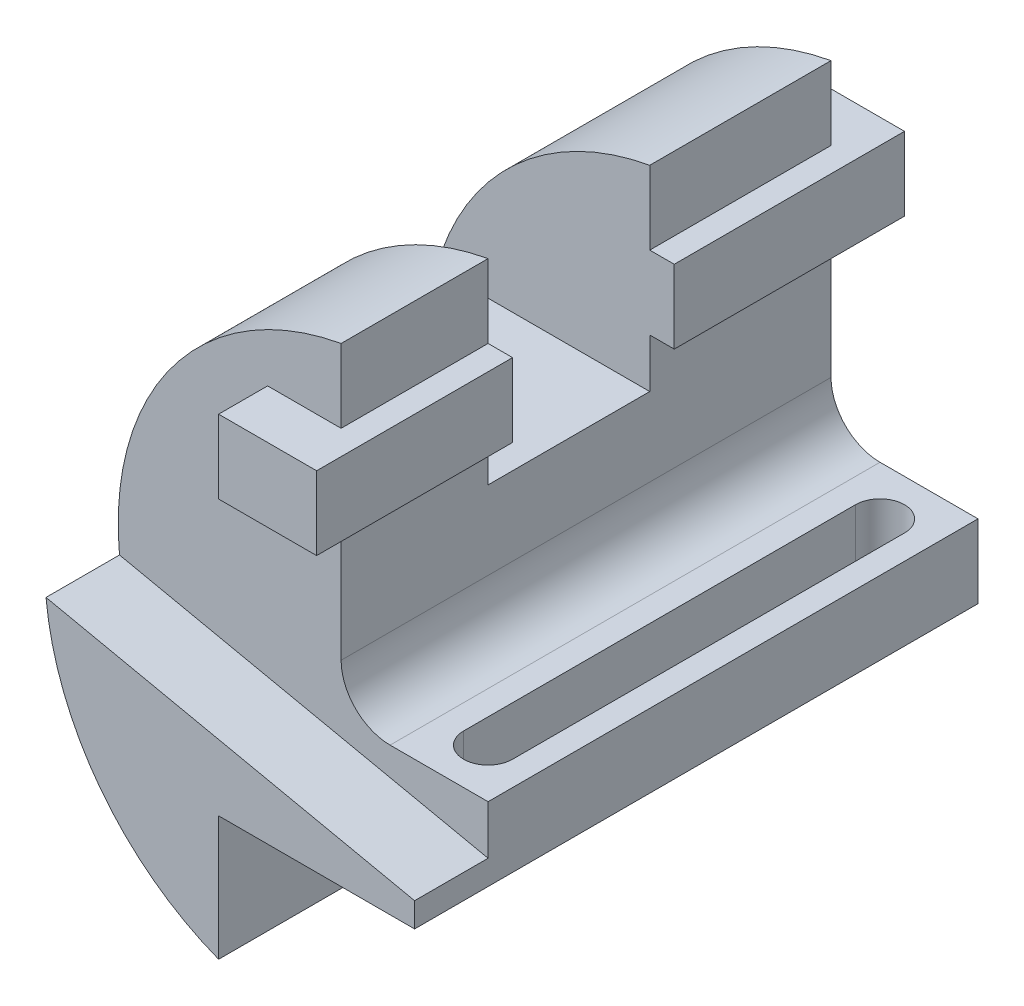
SolidWorks part; units mm, degrees
material "1060 Alloy"
ref_plane "Front Plane" through (0, 0, 0) normal (0, 0, 1) x (1, 0, 0)
ref_plane "Top Plane" through (0, 0, 0) normal (0, 1, 0) x (1, 0, 0)
ref_plane "Right Plane" through (0, 0, 0) normal (1, 0, 0) x (0, 0, -1)
sketch "Sketch1" plane through (0, 0, 0) normal (0, 0, 1) x (1, 0, 0)
  line L0 (0, 0) -> (-40, 0)
  line L1 (-40, 0) -> (-40, -25.3628)
  line L2 (0, 0) -> (0, 15)
  line L3 (0, 15) -> (-20, 15)
  line L4 (-30, 25) -> (-30, 81)
  arc A0 (-40, -25.3628) -> (-30, 81) centre (-20, 26.4083) cw
  arc A1 (-20, 15) -> (-30, 25) centre (-20, 25) cw
  point P10 (-30, 15)
  dimension "D5" = 55.5
  dimension "D7" = 10
  dimension "D1" = 40
  dimension "D2" = 15
  dimension "D3" = 30
  dimension "D4" = 66
  dimension "D6" = 10
extrude "Boss-Extrude1" add sketch "Sketch1" along normal blind 115
sketch "Sketch2" plane through (0, 0, 0) normal (0, 0, -1) x (-1, 0, 0)
  line L0 (30, 25) -> (30, 81) construction
  line L1 (25, 66) -> (45, 66)
  line L2 (25, 66) -> (25, 51)
  line L3 (25, 51) -> (45, 51)
  line L4 (45, 66) -> (45, 51)
  dimension "D1" = 15
  dimension "D2" = 15
  dimension "D3" = 20
  dimension "D4" = 5
sketch "Sketch4" plane through (0, 0, 115) normal (0, 0, 1) x (1, 0, 0)
  line L0 (0, 5) -> (-75.235, 20.9917)
  line L1 (0, 0) -> (0, 15) construction
  line L2 (-40, 0) -> (0, 0) construction
  line L8 (0, 0) -> (0, 15)
  line L9 (0, 15) -> (-20, 15)
  line L10 (-30, 25) -> (-30, 81)
  line L11 (-40, -25.3628) -> (-40, 0)
  line L12 (-40, 0) -> (0, 0)
  line L13 (0, 5) -> (0, 15)
  line L14 (0, 15) -> (-20, 15)
  line L15 (-30, 25) -> (-30, 81)
  arc A2 (-30, 25) -> (-20, 15) centre (-20, 25) ccw
  arc A3 (-30, 81) -> (-40, -25.3628) centre (-20, 26.4083) ccw
  arc A4 (-30, 25) -> (-20, 15) centre (-20, 25) ccw
  arc A5 (-30, 81) -> (-75.235, 20.9917) centre (-20, 26.4083) ccw
  dimension "D1" = 78
  dimension "D2" = 5
  dimension "D3" = 0
extrude "Cut-Extrude2" cut sketch "Sketch4" against normal blind 15
extrude "Boss-Extrude3" add sketch "Sketch2" against normal offset from surface 5 and the other way blind 10 up to face at (-32.3604, -0.8725, 115)
sketch "Sketch7" plane through (-30, 0, 0) normal (1, 0, 0) x (0, 0, -1)
  line L0 (-100, 81) -> (0, 81) construction
  line L1 (-70, 81) -> (-37, 81)
  line L2 (-70, 81) -> (-70, 41)
  line L3 (-70, 41) -> (-37, 41)
  line L4 (-37, 81) -> (-37, 41)
  line L5 (-100, 66) -> (-100, 81) construction
  line L6 (-100, 51) -> (0, 51) construction
  dimension "D1" = 33
  dimension "D2" = 30
  dimension "D3" = 10
extrude "Cut-Extrude3" cut sketch "Sketch7" against normal through all both and the other way through all
sketch "Sketch8" plane through (0, 15, 0) normal (0, 1, 0) x (1, 0, 0)
  line L0 (-10, -10) -> (-10, -90) construction
  line L1 (-5, -10) -> (-5, -90)
  line L2 (-15, -10) -> (-15, -90)
  line L3 (0, -100) -> (-20, -100) construction
  line L4 (0, -100) -> (0, 0) construction
  arc A0 (-5, -10) -> (-15, -10) centre (-10, -10) ccw
  arc A1 (-15, -90) -> (-5, -90) centre (-10, -90) ccw
  point P2 (-10, -50)
  dimension "D1" = 80
  dimension "D2" = 10
  dimension "D3" = 10
  dimension "D4" = 10
extrude "Cut-Extrude4" cut sketch "Sketch8" against normal through all both
equation "\"a\"= 55.5mm"
equation "\"b\"= 66mm"
equation "\"c\"= 33mm"
